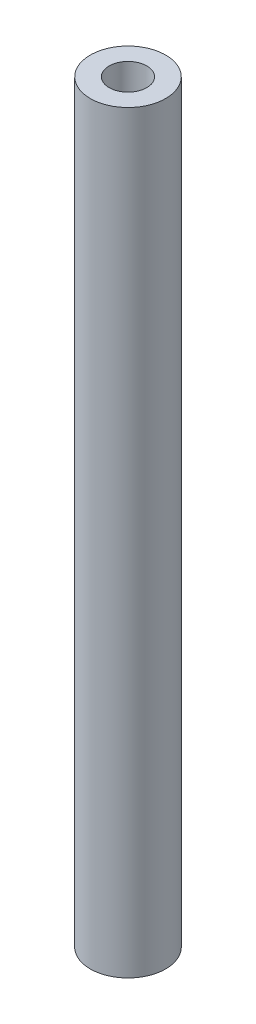
SolidWorks part; units mm, degrees
ref_plane "Front Plane" through (0, 0, 0) normal (0, 0, 1) x (1, 0, 0)
ref_plane "Top Plane" through (0, 0, 0) normal (0, 1, 0) x (1, 0, 0)
ref_plane "Right Plane" through (0, 0, 0) normal (1, 0, 0) x (0, 0, -1)
sketch "Sketch1" plane through (0, 0, 0) normal (0, 1, 0) x (1, 0, 0)
  circle A0 centre (0, 0) radius 4
  circle A1 centre (0, 0) radius 2
  dimension "D1" = 8
  dimension "D2" = 4
extrude "Boss-Extrude1" add sketch "Sketch1" along normal blind 80
